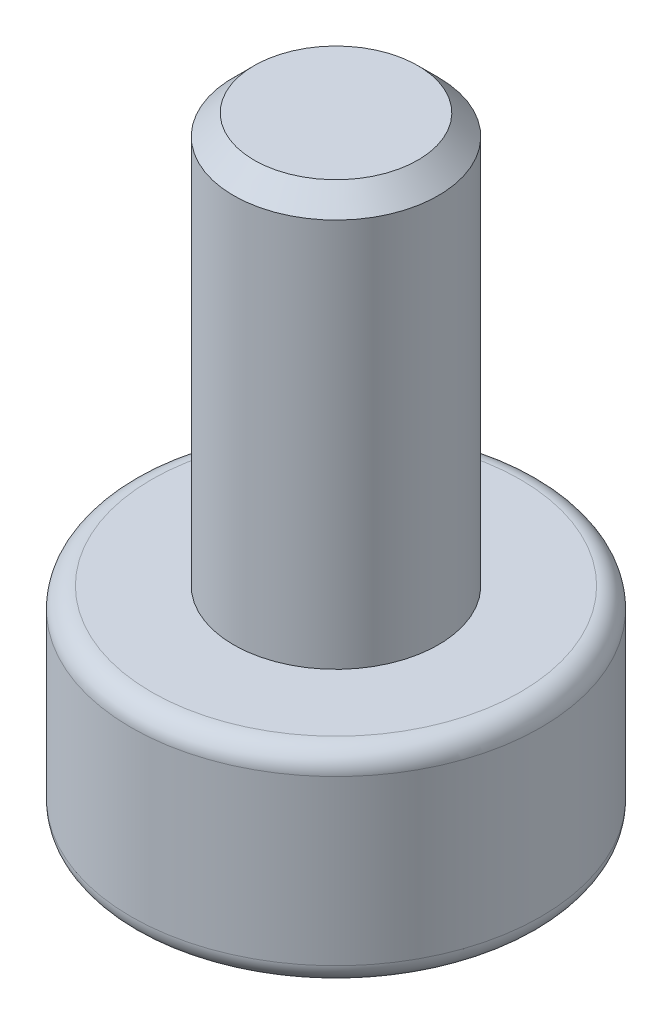
SolidWorks part; units mm, degrees
material "AISI 304"
ref_plane "前视基准面" through (0, 0, 0) normal (0, 0, 1) x (1, 0, 0)
ref_plane "上视基准面" through (0, 0, 0) normal (0, 1, 0) x (1, 0, 0)
ref_plane "右视基准面" through (0, 0, 0) normal (1, 0, 0) x (0, 0, -1)
sketch "草图2" plane through (0, 0, 0) normal (0, 1, 0) x (1, 0, 0)
  circle A0 centre (0, 0) radius 2
  dimension "D1" = 4
extrude "凸台-拉伸1" add sketch "草图2" along normal blind 2
sketch "草图3" plane through (0, 2, 0) normal (0, 1, 0) x (1, 0, 0)
  circle A0 centre (0, 0) radius 1
  dimension "D1" = 2
extrude "凸台-拉伸2" add sketch "草图3" along normal blind 4
fillet "圆角1" radius 0.2 2 edges at (0, 2, 2) (0, 0, 2)
sketch "草图4" plane through (0, 0, 0) normal (0, -1, 0) x (1, 0, 0)
  circle A0 centre (0, 0) radius 0.765
  dimension "D1" = 1.53
extrude "切除-拉伸1" cut sketch "草图4" against normal blind 1.52
chamfer "倒角1" distance 0.1 angle 45 1 edges at (0, 0, -0.765)
chamfer "倒角2" distance 0.2 angle 45 1 edges at (0, 6, 1)
